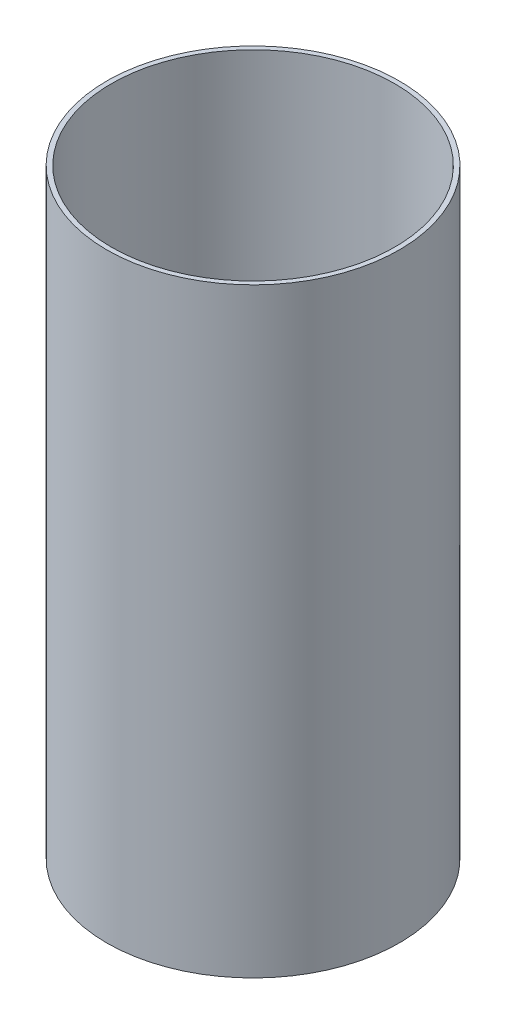
SolidWorks part; units mm, degrees
ref_plane "Front Plane" through (0, 0, 0) normal (0, 0, 1) x (1, 0, 0)
ref_plane "Top Plane" through (0, 0, 0) normal (0, 1, 0) x (1, 0, 0)
ref_plane "Right Plane" through (0, 0, 0) normal (1, 0, 0) x (0, 0, -1)
sketch "Sketch1" plane through (0, 0, 0) normal (0, 1, 0) x (1, 0, 0)
  circle A0 centre (0, 0) radius 49.53
  circle A1 centre (0, 0) radius 47.9552
  dimension "D1" = 99.06
  dimension "D2" = 95.9104
extrude "Boss-Extrude1" add sketch "Sketch1" along normal blind 203.2
